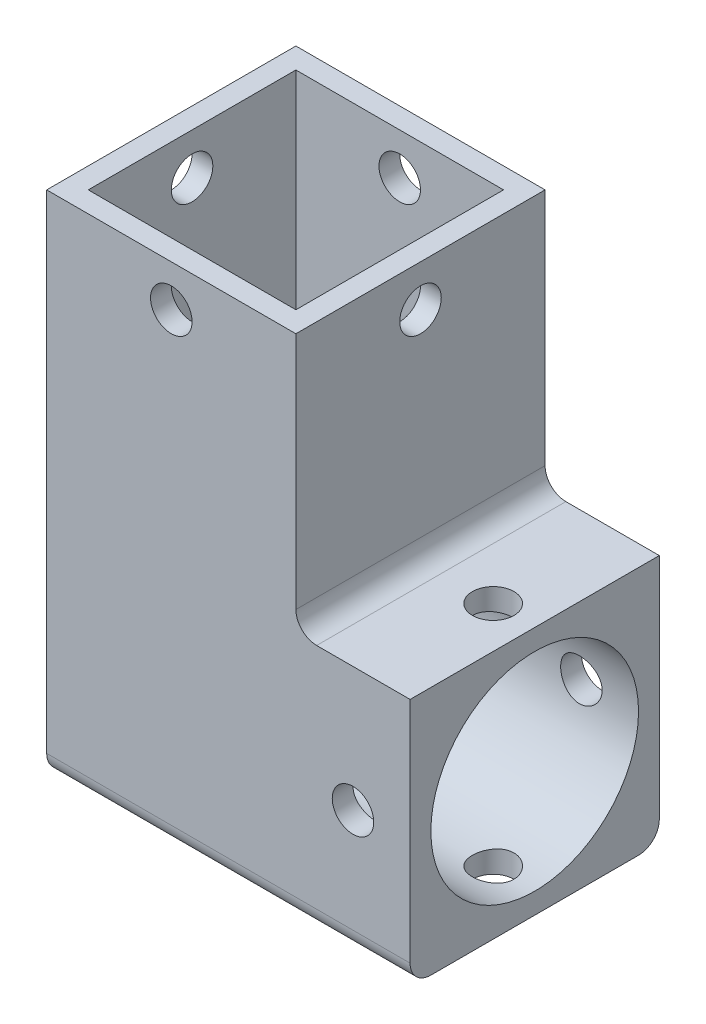
SolidWorks part; units mm, degrees
material "ABS"
ref_plane "Front Plane" through (0, 0, 0) normal (0, 0, 1) x (1, 0, 0)
ref_plane "Top Plane" through (0, 0, 0) normal (0, 1, 0) x (1, 0, 0)
ref_plane "Right Plane" through (0, 0, 0) normal (1, 0, 0) x (0, 0, -1)
sketch "Sketch1" plane through (0, 0, 0) normal (0, 0, 1) x (1, 0, 0)
  line L0 (-35, 25) -> (-35, -24)
  line L1 (0, 0) -> (-11, 0)
  line L2 (0, 0) -> (0, -24)
  line L3 (0, -24) -> (-35, -24)
  line L7 (-35, 25) -> (-11, 25)
  line L8 (-11, 0) -> (-11, 25)
  dimension "D1" = 24
  dimension "D2" = 24
  dimension "D3" = 35
  dimension "D4" = 25
extrude "Boss-Extrude1" add sketch "Sketch1" along normal blind 24
sketch "Sketch2" plane through (0, 25, 0) normal (0, 1, 0) x (1, 0, 0)
  line L0 (-35, -12) -> (-23, -12) construction
  line L1 (-35, -24) -> (-35, 0) construction
  line L2 (-23, -12) -> (-23, -24) construction
  line L3 (-11, -24) -> (-35, -24) construction
  line L5 (-13, -22) -> (-33, -22)
  line L6 (-13, -22) -> (-13, -2)
  line L7 (-13, -2) -> (-33, -2)
  line L8 (-33, -22) -> (-33, -2)
  line L9 (-13, -22) -> (-33, -2) construction
  line L10 (-13, -2) -> (-33, -22) construction
  dimension "D1" = 20
  dimension "D2" = 20
extrude "Cut-Extrude2" cut sketch "Sketch2" against normal blind 25
sketch "Sketch3" plane through (0, 0, 0) normal (1, 0, 0) x (0, 0, -1)
  line L0 (-12, -24) -> (-12, -12) construction
  line L1 (-24, -24) -> (0, -24) construction
  line L2 (-12, -12) -> (0, -12) construction
  line L3 (0, -24) -> (0, 0) construction
  circle A0 centre (-12, -12) radius 10
  dimension "D1" = 20
extrude "Cut-Extrude3" cut sketch "Sketch3" against normal through all
sketch "Sketch4" plane through (-11, 0, 0) normal (1, 0, 0) x (0, 0, -1)
  line L0 (-12, 25) -> (-12, 21) construction
  line L1 (-24, 25) -> (0, 25) construction
  line L2 (-12, 21) -> (0, 21) construction
  line L3 (0, 0) -> (0, 25) construction
  circle A0 centre (-12, 21) radius 2
  dimension "D2" = 4
  dimension "D1" = 4
extrude "Cut-Extrude4" cut sketch "Sketch4" against normal blind 25
sketch "Sketch5" plane through (0, 0, 0) normal (0, 0, -1) x (-1, 0, 0)
  line L0 (23, 25) -> (23, 21) construction
  line L1 (11, 25) -> (35, 25) construction
  line L2 (23, 21) -> (35, 21) construction
  line L3 (35, 25) -> (35, -24) construction
  circle A0 centre (23, 21) radius 2
  dimension "D2" = 4
  dimension "D1" = 4
extrude "Cut-Extrude5" cut sketch "Sketch5" against normal blind 25
sketch "Sketch6" plane through (0, 0, 0) normal (0, 1, 0) x (1, 0, 0)
  line L0 (0, -12) -> (-4, -12) construction
  line L1 (0, -24) -> (0, 0) construction
  line L2 (-4, -12) -> (-4, 0) construction
  circle A0 centre (-4, -12) radius 2
  dimension "D2" = 4
  dimension "D1" = 4
extrude "Cut-Extrude6" cut sketch "Sketch6" against normal blind 25
sketch "Sketch7" plane through (0, 0, 0) normal (0, 0, -1) x (-1, 0, 0)
  line L0 (5.5, 0) -> (5.5, -12) construction
  line L1 (0, 0) -> (11, 0) construction
  line L2 (5.5, -12) -> (0, -12) construction
  line L3 (0, -24) -> (0, 0) construction
  circle A0 centre (5.5, -12) radius 2
  dimension "D1" = 4
extrude "Cut-Extrude7" cut sketch "Sketch7" against normal blind 25
fillet "Fillet1" radius 2 3 edges at (-17.5, -24, 24) (-17.5, -24, 0) (-11, 0, 12)
